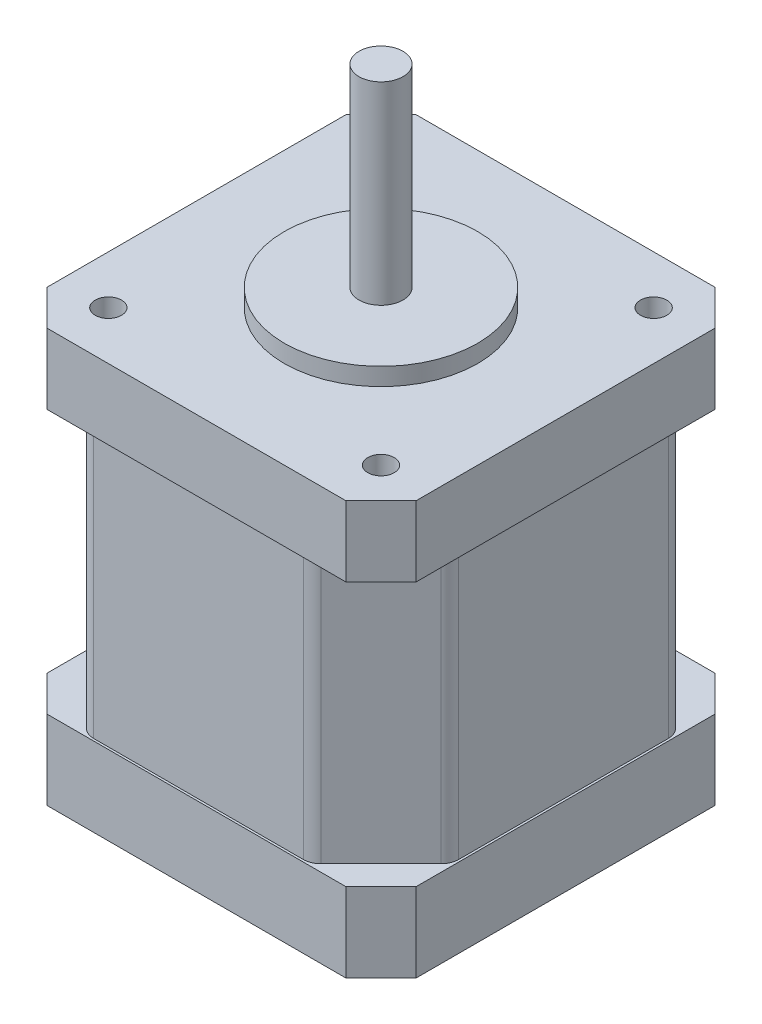
SolidWorks part; units mm, degrees
material "Commercially Pure CP-Ti UNS R50700  Grade 4 (SS)"
ref_plane "Front Plane" through (0, 0, 0) normal (0, 0, 1) x (1, 0, 0)
ref_plane "Top Plane" through (0, 0, 0) normal (0, 1, 0) x (1, 0, 0)
ref_plane "Right Plane" through (0, 0, 0) normal (1, 0, 0) x (0, 0, -1)
sketch "Sketch1" plane through (0, 0, 0) normal (0, 1, 0) x (1, 0, 0)
  line L0 (-21, 21) -> (21, -21) construction
  line L1 (-17, 21) -> (17, 21)
  line L2 (-21, 17) -> (-21, -17)
  line L3 (-17, -21) -> (17, -21)
  line L4 (21, 17) -> (21, -17)
  line L5 (-21, 17) -> (-17, 21)
  line L6 (-21, -17) -> (-17, -21)
  line L7 (17, -21) -> (21, -17)
  line L8 (17, 21) -> (21, 17)
  line L9 (-15.5, 15.5) -> (15.5, 15.5) construction
  line L10 (15.5, 15.5) -> (15.5, -15.5) construction
  line L11 (15.5, -15.5) -> (-15.5, -15.5) construction
  line L12 (-15.5, -15.5) -> (-15.5, 15.5) construction
  line L13 (15.5, 15.5) -> (-15.5, -15.5) construction
  circle A0 centre (-15.5, 15.5) radius 1.5
  circle A1 centre (-15.5, -15.5) radius 1.5
  circle A2 centre (15.5, -15.5) radius 1.5
  circle A3 centre (15.5, 15.5) radius 1.5
  point P2 (-21, -21)
  point P3 (21, 21)
  dimension "D2" = 3
  dimension "D3" = 31
  dimension "D1" = 42
extrude "Boss-Extrude1" add sketch "Sketch1" along normal blind 8
sketch "Sketch2" plane through (0, 0, 0) normal (0, -1, 0) x (1, 0, 0)
  line L1 (-12.75, 20.75) -> (12.75, 20.75)
  line L2 (-20.75, 12.75) -> (-20.75, -12.75)
  line L3 (-12.75, -20.75) -> (12.75, -20.75)
  line L4 (20.75, 12.75) -> (20.75, -12.75)
  line L9 (12.75, 20.75) -> (20.75, 12.75)
  line L10 (12.75, -20.75) -> (20.75, -12.75)
  line L11 (-20.75, -12.75) -> (-12.75, -20.75)
  line L12 (-20.75, 12.75) -> (-12.75, 20.75)
  line L13 (0, -20.75) -> (0, 0) construction
  line L14 (0, 0) -> (-20.75, 0) construction
  point P0 (-20.75, 20.75)
  point P1 (20.75, -20.75)
  point P2 (-20.75, -20.75)
  point P3 (20.75, 20.75)
  dimension "D2" = 41.5
extrude "Boss-Extrude2" add sketch "Sketch2" along normal blind 30
fillet "Fillet1" radius 2 8 edges at (12.75, -15, 20.75) (20.75, -15, 12.75) (20.75, -15, -12.75) (12.75, -15, -20.75) (-12.75, -15, -20.75) (-20.75, -15, -12.75) (-20.75, -15, 12.75) (-12.75, -15, 20.75)
sketch "Sketch3" plane through (0, -30, 0) normal (0, -1, 0) x (1, 0, 0)
  line L0 (-21, 17) -> (-21, -17)
  line L1 (-21, -17) -> (-17, -21)
  line L2 (-17, -21) -> (17, -21)
  line L3 (17, -21) -> (21, -17)
  line L4 (21, -17) -> (21, 17)
  line L5 (21, 17) -> (17, 21)
  line L6 (17, 21) -> (-17, 21)
  line L7 (-17, 21) -> (-21, 17)
extrude "Boss-Extrude3" add sketch "Sketch3" along normal blind 9
sketch "Sketch4" plane through (0, 8, 0) normal (0, 1, 0) x (1, 0, 0)
  circle A0 centre (0, 0) radius 11
  dimension "D1" = 22
extrude "Boss-Extrude4" add sketch "Sketch4" along normal blind 2
sketch "Sketch5" plane through (0, 10, 0) normal (0, 1, 0) x (1, 0, 0)
  circle A0 centre (0, 0) radius 2.5
  dimension "D1" = 5
extrude "Boss-Extrude5" add sketch "Sketch5" along normal blind 22
sketch "Sketch6" plane through (0, -39, 0) normal (0, -1, 0) x (1, 0, 0)
  circle A0 centre (0, 0) radius 2.5
  circle A1 centre (0, 0) radius 2.5 construction
extrude "Boss-Extrude6" add sketch "Sketch6" along normal blind 10
